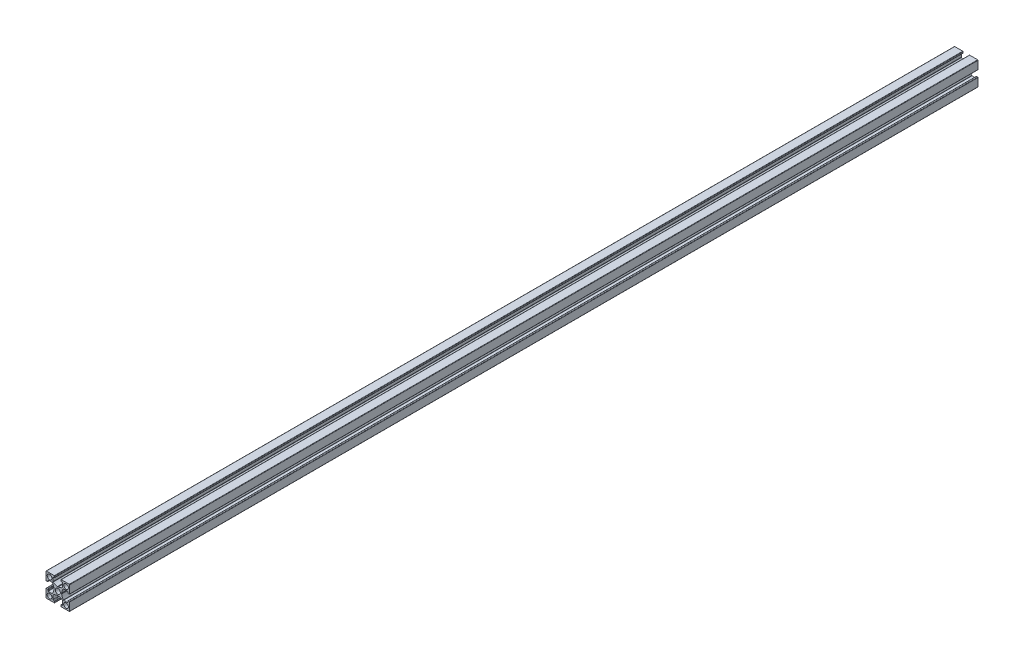
SolidWorks part; units mm, degrees
ref_plane "정면" through (0, 0, 0) normal (0, 0, 1) x (1, 0, 0)
ref_plane "윗면" through (0, 0, 0) normal (0, 1, 0) x (1, 0, 0)
ref_plane "우측면" through (0, 0, 0) normal (1, 0, 0) x (0, 0, -1)
sketch "Model" plane through (0, 0, 0) normal (0, 0, 1) x (1, 0, 0)
  line L0 (2292.4151, 1187.1915) -> (2314.8128, 1187.1915) construction
  line L1 (2307.7639, 1192.1343) -> (2307.7639, 1195.3915)
  line L2 (2307.4639, 1195.6915) -> (2306.5639, 1195.6915)
  line L3 (2306.2639, 1195.9915) -> (2306.2639, 1196.8915)
  line L4 (2306.5639, 1197.1915) -> (2313.3139, 1197.1915)
  line L5 (2313.6139, 1196.8915) -> (2313.6139, 1190.1415)
  line L6 (2313.3139, 1189.8415) -> (2312.4139, 1189.8415)
  line L7 (2312.1139, 1190.1415) -> (2312.1139, 1191.0415)
  line L8 (2311.8139, 1191.3415) -> (2308.5567, 1191.3415)
  line L9 (2306.9212, 1187.4988) -> (2306.6139, 1187.1915)
  line L10 (2306.6139, 1187.1915) -> (2306.9212, 1186.8843)
  line L11 (2308.5567, 1183.0415) -> (2311.8139, 1183.0415)
  line L12 (2312.1139, 1183.3415) -> (2312.1139, 1184.2415)
  line L13 (2312.4139, 1184.5415) -> (2313.3139, 1184.5415)
  line L14 (2313.6139, 1184.2415) -> (2313.6139, 1177.4915)
  line L15 (2313.3139, 1177.1915) -> (2306.5639, 1177.1915)
  line L16 (2306.2639, 1177.4915) -> (2306.2639, 1178.3915)
  line L17 (2306.5639, 1178.6915) -> (2307.4639, 1178.6915)
  line L18 (2307.7639, 1178.9915) -> (2307.7639, 1182.2488)
  line L19 (2303.9212, 1183.8843) -> (2303.6139, 1184.1915)
  line L20 (2303.6139, 1184.1915) -> (2303.3066, 1183.8843)
  line L21 (2299.4639, 1182.2488) -> (2299.4639, 1178.9915)
  line L22 (2299.7639, 1178.6915) -> (2300.6639, 1178.6915)
  line L23 (2300.9639, 1178.3915) -> (2300.9639, 1177.4915)
  line L24 (2300.6639, 1177.1915) -> (2293.9139, 1177.1915)
  line L25 (2293.6139, 1177.4915) -> (2293.6139, 1184.2415)
  line L26 (2293.9139, 1184.5415) -> (2294.8139, 1184.5415)
  line L27 (2295.1139, 1184.2415) -> (2295.1139, 1183.3415)
  line L28 (2295.4139, 1183.0415) -> (2298.6712, 1183.0415)
  line L29 (2300.3066, 1186.8843) -> (2300.6139, 1187.1915)
  line L30 (2300.6139, 1187.1915) -> (2300.3066, 1187.4988)
  line L31 (2298.6712, 1191.3415) -> (2295.4139, 1191.3415)
  line L32 (2295.1139, 1191.0415) -> (2295.1139, 1190.1415)
  line L33 (2294.8139, 1189.8415) -> (2293.9139, 1189.8415)
  line L34 (2293.6139, 1190.1415) -> (2293.6139, 1196.8915)
  line L35 (2293.9139, 1197.1915) -> (2300.6639, 1197.1915)
  line L36 (2300.9639, 1196.8915) -> (2300.9639, 1195.9915)
  line L37 (2300.6639, 1195.6915) -> (2299.7639, 1195.6915)
  line L38 (2299.4639, 1195.3915) -> (2299.4639, 1192.1343)
  line L39 (2303.3066, 1190.4988) -> (2303.6139, 1190.1915)
  line L40 (2303.6139, 1190.1915) -> (2303.9212, 1190.4988)
  line L41 (2294.1139, 1194.1915) -> (2299.1139, 1194.1915) construction
  line L42 (2296.6139, 1196.6915) -> (2296.6139, 1191.6915) construction
  line L43 (2294.1139, 1180.1915) -> (2299.1139, 1180.1915) construction
  line L44 (2296.6139, 1177.6915) -> (2296.6139, 1182.6915) construction
  line L45 (2303.6139, 1198.3904) -> (2303.6139, 1175.9927) construction
  line L46 (2313.1139, 1194.1915) -> (2308.1139, 1194.1915) construction
  line L47 (2310.6139, 1196.6915) -> (2310.6139, 1191.6915) construction
  line L48 (2310.6139, 1177.6915) -> (2310.6139, 1182.6915) construction
  line L49 (2313.1139, 1180.1915) -> (2308.1139, 1180.1915) construction
  circle A0 centre (2303.6139, 1187.1915) radius 2.15
  circle A1 centre (2296.6139, 1194.1915) radius 2
  circle A2 centre (2296.6139, 1180.1915) radius 2
  circle A3 centre (2310.6139, 1194.1915) radius 2
  circle A4 centre (2310.6139, 1180.1915) radius 2
  arc A5 (2307.7639, 1195.3915) -> (2307.4639, 1195.6915) centre (2307.4639, 1195.3915) ccw
  arc A6 (2306.2639, 1195.9915) -> (2306.5639, 1195.6915) centre (2306.5639, 1195.9915) ccw
  arc A7 (2306.5639, 1197.1915) -> (2306.2639, 1196.8915) centre (2306.5639, 1196.8915) ccw
  arc A8 (2313.6139, 1196.8915) -> (2313.3139, 1197.1915) centre (2313.3139, 1196.8915) ccw
  arc A9 (2313.3139, 1189.8415) -> (2313.6139, 1190.1415) centre (2313.3139, 1190.1415) ccw
  arc A10 (2312.1139, 1190.1415) -> (2312.4139, 1189.8415) centre (2312.4139, 1190.1415) ccw
  arc A11 (2312.1139, 1191.0415) -> (2311.8139, 1191.3415) centre (2311.8139, 1191.0415) ccw
  arc A12 (2308.5567, 1191.3415) -> (2308.3217, 1191.2281) centre (2308.5567, 1191.0415) ccw
  arc A13 (2308.3217, 1191.2281) -> (2306.9212, 1187.4988) centre (2313.4048, 1187.1915) ccw
  arc A14 (2306.9212, 1186.8843) -> (2308.3217, 1183.155) centre (2313.4048, 1187.1915) ccw
  arc A15 (2308.3217, 1183.155) -> (2308.5567, 1183.0415) centre (2308.5567, 1183.3415) ccw
  arc A16 (2311.8139, 1183.0415) -> (2312.1139, 1183.3415) centre (2311.8139, 1183.3415) ccw
  arc A17 (2312.4139, 1184.5415) -> (2312.1139, 1184.2415) centre (2312.4139, 1184.2415) ccw
  arc A18 (2313.6139, 1184.2415) -> (2313.3139, 1184.5415) centre (2313.3139, 1184.2415) ccw
  arc A19 (2313.3139, 1177.1915) -> (2313.6139, 1177.4915) centre (2313.3139, 1177.4915) ccw
  arc A20 (2306.2639, 1177.4915) -> (2306.5639, 1177.1915) centre (2306.5639, 1177.4915) ccw
  arc A21 (2306.5639, 1178.6915) -> (2306.2639, 1178.3915) centre (2306.5639, 1178.3915) ccw
  arc A22 (2307.4639, 1178.6915) -> (2307.7639, 1178.9915) centre (2307.4639, 1178.9915) ccw
  arc A23 (2307.7639, 1182.2488) -> (2307.6505, 1182.4837) centre (2307.4639, 1182.2488) ccw
  arc A24 (2307.6505, 1182.4837) -> (2303.9212, 1183.8843) centre (2303.6139, 1177.4007) ccw
  arc A25 (2303.3066, 1183.8843) -> (2299.5774, 1182.4837) centre (2303.6139, 1177.4007) ccw
  arc A26 (2299.5774, 1182.4837) -> (2299.4639, 1182.2488) centre (2299.7639, 1182.2488) ccw
  arc A27 (2299.4639, 1178.9915) -> (2299.7639, 1178.6915) centre (2299.7639, 1178.9915) ccw
  arc A28 (2300.9639, 1178.3915) -> (2300.6639, 1178.6915) centre (2300.6639, 1178.3915) ccw
  arc A29 (2300.6639, 1177.1915) -> (2300.9639, 1177.4915) centre (2300.6639, 1177.4915) ccw
  arc A30 (2293.6139, 1177.4915) -> (2293.9139, 1177.1915) centre (2293.9139, 1177.4915) ccw
  arc A31 (2293.9139, 1184.5415) -> (2293.6139, 1184.2415) centre (2293.9139, 1184.2415) ccw
  arc A32 (2295.1139, 1184.2415) -> (2294.8139, 1184.5415) centre (2294.8139, 1184.2415) ccw
  arc A33 (2295.1139, 1183.3415) -> (2295.4139, 1183.0415) centre (2295.4139, 1183.3415) ccw
  arc A34 (2298.6712, 1183.0415) -> (2298.9061, 1183.155) centre (2298.6712, 1183.3415) ccw
  arc A35 (2298.9061, 1183.155) -> (2300.3066, 1186.8843) centre (2293.8231, 1187.1915) ccw
  arc A36 (2300.3066, 1187.4988) -> (2298.9061, 1191.2281) centre (2293.8231, 1187.1915) ccw
  arc A37 (2298.9061, 1191.2281) -> (2298.6712, 1191.3415) centre (2298.6712, 1191.0415) ccw
  arc A38 (2295.4139, 1191.3415) -> (2295.1139, 1191.0415) centre (2295.4139, 1191.0415) ccw
  arc A39 (2294.8139, 1189.8415) -> (2295.1139, 1190.1415) centre (2294.8139, 1190.1415) ccw
  arc A40 (2293.6139, 1190.1415) -> (2293.9139, 1189.8415) centre (2293.9139, 1190.1415) ccw
  arc A41 (2293.9139, 1197.1915) -> (2293.6139, 1196.8915) centre (2293.9139, 1196.8915) ccw
  arc A42 (2300.9639, 1196.8915) -> (2300.6639, 1197.1915) centre (2300.6639, 1196.8915) ccw
  arc A43 (2300.6639, 1195.6915) -> (2300.9639, 1195.9915) centre (2300.6639, 1195.9915) ccw
  arc A44 (2299.7639, 1195.6915) -> (2299.4639, 1195.3915) centre (2299.7639, 1195.3915) ccw
  arc A45 (2299.4639, 1192.1343) -> (2299.5774, 1191.8994) centre (2299.7639, 1192.1343) ccw
  arc A46 (2299.5774, 1191.8994) -> (2303.3066, 1190.4988) centre (2303.6139, 1196.9824) ccw
  arc A47 (2303.9212, 1190.4988) -> (2307.6505, 1191.8994) centre (2303.6139, 1196.9824) ccw
  arc A48 (2307.6505, 1191.8994) -> (2307.7639, 1192.1343) centre (2307.4639, 1192.1343) ccw
extrude "보스-돌출1" add sketch "Model" along normal blind 770
